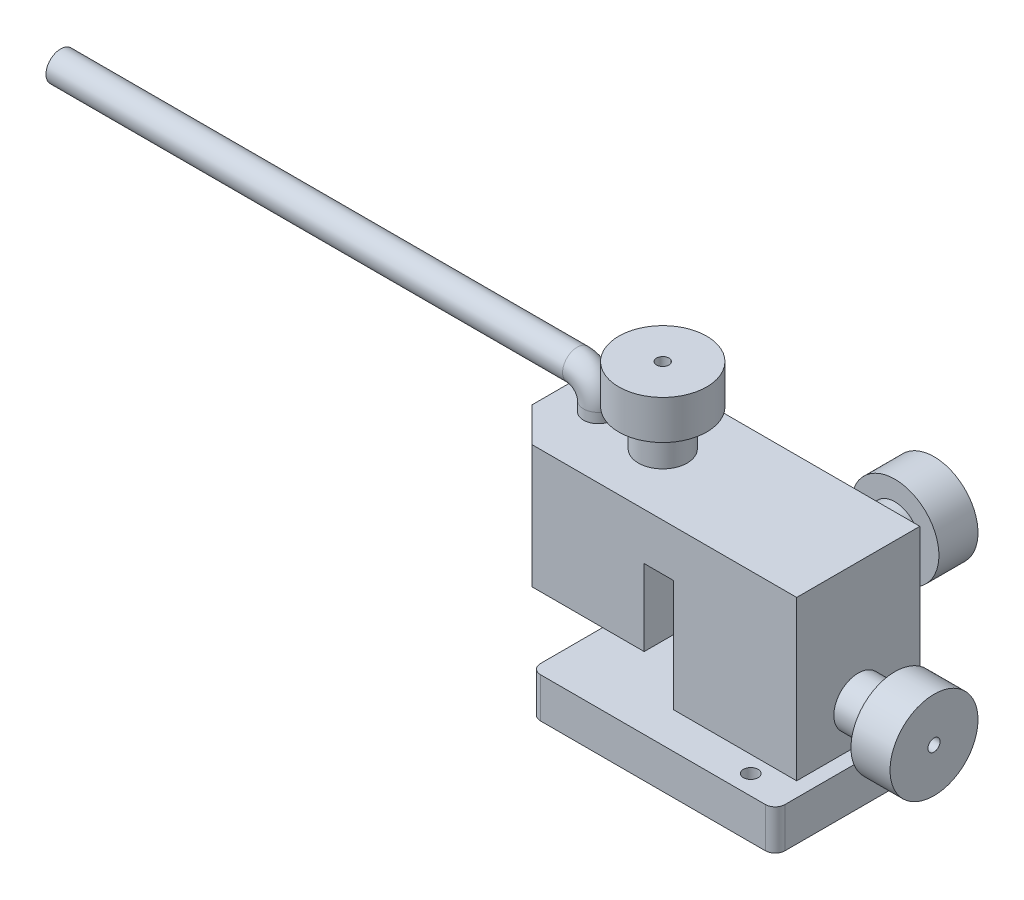
SolidWorks part; units mm, degrees
ref_plane "Front Plane" through (0, 0, 0) normal (0, 0, 1) x (1, 0, 0)
ref_plane "Top Plane" through (0, 0, 0) normal (0, 1, 0) x (1, 0, 0)
ref_plane "Right Plane" through (0, 0, 0) normal (1, 0, 0) x (0, 0, -1)
sketch "Sketch1" plane through (0, 0, 0) normal (0, 1, 0) x (1, 0, 0)
  line L1 (2, 0) -> (48, 0)
  line L2 (0, 2) -> (0, 38)
  line L3 (2, 40) -> (48, 40)
  line L4 (50, 2) -> (50, 38)
  arc A0 (2, 0) -> (0, 2) centre (2, 2) cw
  arc A1 (48, 0) -> (50, 2) centre (48, 2) ccw
  arc A2 (48, 40) -> (50, 38) centre (48, 38) cw
  arc A3 (0, 38) -> (2, 40) centre (2, 38) cw
  point P7 (0, 0)
  point P10 (50, 0)
  point P13 (50, 40)
  dimension "D3" = 2
  dimension "D1" = 50
  dimension "D2" = 40
extrude "Boss-Extrude1" add sketch "Sketch1" along normal blind 8.2
sketch "Sketch2" plane through (0, 8.2, 0) normal (0, 1, 0) x (1, 0, 0)
  line L0 (0, 20) -> (50, 20) construction
  line L1 (21.8, 32.6) -> (47, 32.6)
  line L2 (21.8, 32.6) -> (21.8, 7.4)
  line L3 (21.8, 7.4) -> (47, 7.4)
  line L4 (47, 32.6) -> (47, 7.4)
  line L5 (0, 38) -> (0, 2) construction
  line L6 (50, 2) -> (50, 38) construction
  dimension "D1" = 25.2
  dimension "D2" = 25.2
  dimension "D3" = 3
extrude "Boss-Extrude2" add sketch "Sketch2" along normal blind 32.5
sketch "Sketch3" plane through (21.8, 0, 0) normal (-1, 0, 0) x (0, 0, 1)
  line L0 (-7.4, 40.7) -> (-7.4, 8.2) construction
  line L1 (-32.6, 40.7) -> (-7.4, 40.7)
  line L2 (-32.6, 40.7) -> (-32.6, 31.1)
  line L3 (-32.6, 31.1) -> (-7.4, 31.1)
  line L4 (-7.4, 40.7) -> (-7.4, 31.1)
  dimension "D1" = 9.6
extrude "Boss-Extrude3" add sketch "Sketch3" along normal blind 6
sketch "Sketch4" plane through (15.8, 0, 0) normal (-1, 0, 0) x (0, 0, 1)
  line L0 (-7.4, 31.1) -> (-7.4, 8.2) construction
  line L1 (-32.6, 40.7) -> (-7.4, 40.7)
  line L2 (-32.6, 40.7) -> (-32.6, 15.5)
  line L3 (-32.6, 15.5) -> (-7.4, 15.5)
  line L4 (-7.4, 40.7) -> (-7.4, 15.5)
  dimension "D1" = 25.2
extrude "Boss-Extrude4" add sketch "Sketch4" along normal blind 30
chamfer "Chamfer1" distance 7 angle 45 2 edges at (-14.2, 28.1, -7.4) (-14.2, 28.1, -32.6)
sketch "Sketch5" plane through (47, 0, 0) normal (1, 0, 0) x (0, 0, -1)
  line L0 (20, 40.7) -> (20, 0) construction
  line L1 (7.4, 40.7) -> (32.6, 40.7) construction
  line L2 (2, 0) -> (38, 0) construction
  circle A0 centre (20, 16) radius 5
  dimension "D1" = 10
  dimension "D2" = 16
extrude "Boss-Extrude5" add sketch "Sketch5" along normal blind 7.5
sketch "Sketch6" plane through (54.5, 0, 0) normal (1, 0, 0) x (0, 0, -1)
  circle A0 centre (20, 16) radius 9
  dimension "D1" = 18
extrude "Boss-Extrude6" add sketch "Sketch6" along normal blind 8
sketch "Sketch7" plane through (62.5, 0, 0) normal (1, 0, 0) x (0, 0, -1)
  circle A0 centre (20, 16) radius 1.25
  dimension "D1" = 2.5
extrude "Cut-Extrude1" cut sketch "Sketch7" against normal blind 4
sketch "Sketch8" plane through (0, 0, -32.6) normal (0, 0, -1) x (-1, 0, 0)
  line L5 (-34.4, 8.2) -> (-34.4, 40.7) construction
  line L6 (-47, 8.2) -> (-21.8, 8.2) construction
  line L7 (-47, 40.7) -> (7.2, 40.7) construction
  line L8 (-48, 0) -> (-2, 0) construction
  circle A0 centre (-34.4, 30) radius 5
  dimension "D1" = 10
  dimension "D2" = 30
extrude "Boss-Extrude7" add sketch "Sketch8" along normal blind 7.5
sketch "Sketch9" plane through (0, 0, -40.1) normal (0, 0, -1) x (-1, 0, 0)
  circle A0 centre (-34.4, 30) radius 9
  dimension "D1" = 18
extrude "Boss-Extrude8" add sketch "Sketch9" along normal blind 8
sketch "Sketch10" plane through (0, 0, -48.1) normal (0, 0, -1) x (-1, 0, 0)
  circle A0 centre (-34.4, 30) radius 1.25
  dimension "D1" = 2.5
extrude "Cut-Extrude2" cut sketch "Sketch10" against normal blind 4
sketch "Sketch11" plane through (0, 40.7, 0) normal (0, 1, 0) x (1, 0, 0)
  line L0 (47, 20) -> (-14.2, 20) construction
  line L1 (47, 7.4) -> (47, 32.6) construction
  line L2 (-14.2, 14.4) -> (-14.2, 25.6) construction
  circle A0 centre (7, 20) radius 5
  dimension "D1" = 10
  dimension "D2" = 40
extrude "Boss-Extrude9" add sketch "Sketch11" along normal blind 7.5
sketch "Sketch12" plane through (0, 48.2, 0) normal (0, 1, 0) x (1, 0, 0)
  circle A0 centre (7, 20) radius 9
  dimension "D1" = 18
extrude "Boss-Extrude10" add sketch "Sketch12" along normal blind 8
sketch "Sketch13" plane through (0, 56.2, 0) normal (0, 1, 0) x (1, 0, 0)
  circle A0 centre (7, 20) radius 1.25
  dimension "D1" = 2.5
extrude "Cut-Extrude3" cut sketch "Sketch13" against normal blind 4
ref_plane "Plane1" through (0, 0, -20) normal (0, 0, 1) x (1, 0, 0)
sketch "Sketch14" plane through (0, 0, -20) normal (0, 0, 1) x (1, 0, 0)
  line L0 (-6.2, 40.7) -> (-6.2, 42.7)
  line L1 (-7.2, 40.7) -> (47, 40.7) construction
  line L2 (-10.5, 47) -> (-116.2, 47)
  arc A0 (-6.2, 42.7) -> (-10.5, 47) centre (-10.5, 42.7) ccw
  dimension "D1" = 6.3
  dimension "D2" = 2
  dimension "D3" = 110
  dimension "D4" = 8
ref_plane "Plane2" through (-116.2, 0, 0) normal (1, 0, 0) x (0, 0, -1)
sketch "Sketch15" plane through (-116.2, 0, 0) normal (1, 0, 0) x (0, 0, -1)
  circle A0 centre (20, 47) radius 3
  dimension "D1" = 6
sweep "Sweep1" add profiles "Sketch15" path "Sketch14"
sketch "Sketch16" plane through (0, 0, 0) normal (0, -1, 0) x (1, 0, 0)
  line L0 (50, -2) -> (50, -38) construction
  line L1 (2, 0) -> (48, 0) construction
  line L2 (48, -40) -> (2, -40) construction
  circle A0 centre (41, -4) radius 1.5
  circle A1 centre (41, -36) radius 1.5
  dimension "D1" = 3
  dimension "D4" = 3
  dimension "D2" = 9
  dimension "D3" = 4
  dimension "D5" = 9
  dimension "D6" = 4
extrude "Cut-Extrude4" cut sketch "Sketch16" against normal up to next
